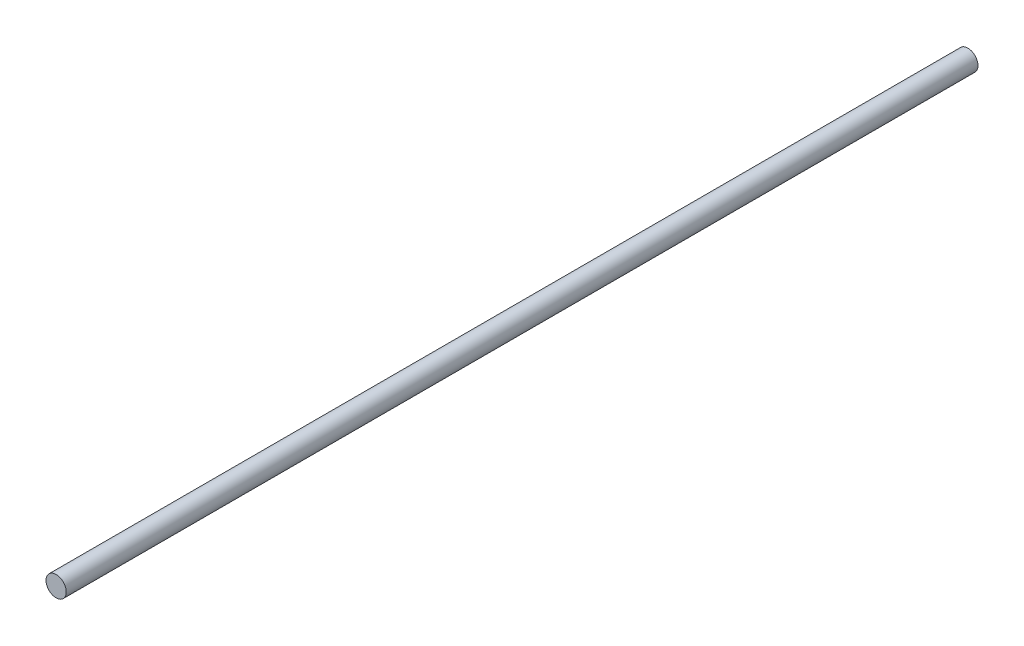
SolidWorks part; units mm, degrees
ref_plane "Front Plane" through (0, 0, 0) normal (0, 0, 1) x (1, 0, 0)
ref_plane "Top Plane" through (0, 0, 0) normal (0, 1, 0) x (1, 0, 0)
ref_plane "Right Plane" through (0, 0, 0) normal (1, 0, 0) x (0, 0, -1)
sketch "Sketch1" plane through (0, 0, 0) normal (0, 0, 1) x (1, 0, 0)
  circle A0 centre (0, 0) radius 1.5
  dimension "D1" = 3
extrude "Boss-Extrude1" add sketch "Sketch1" along normal blind 135
